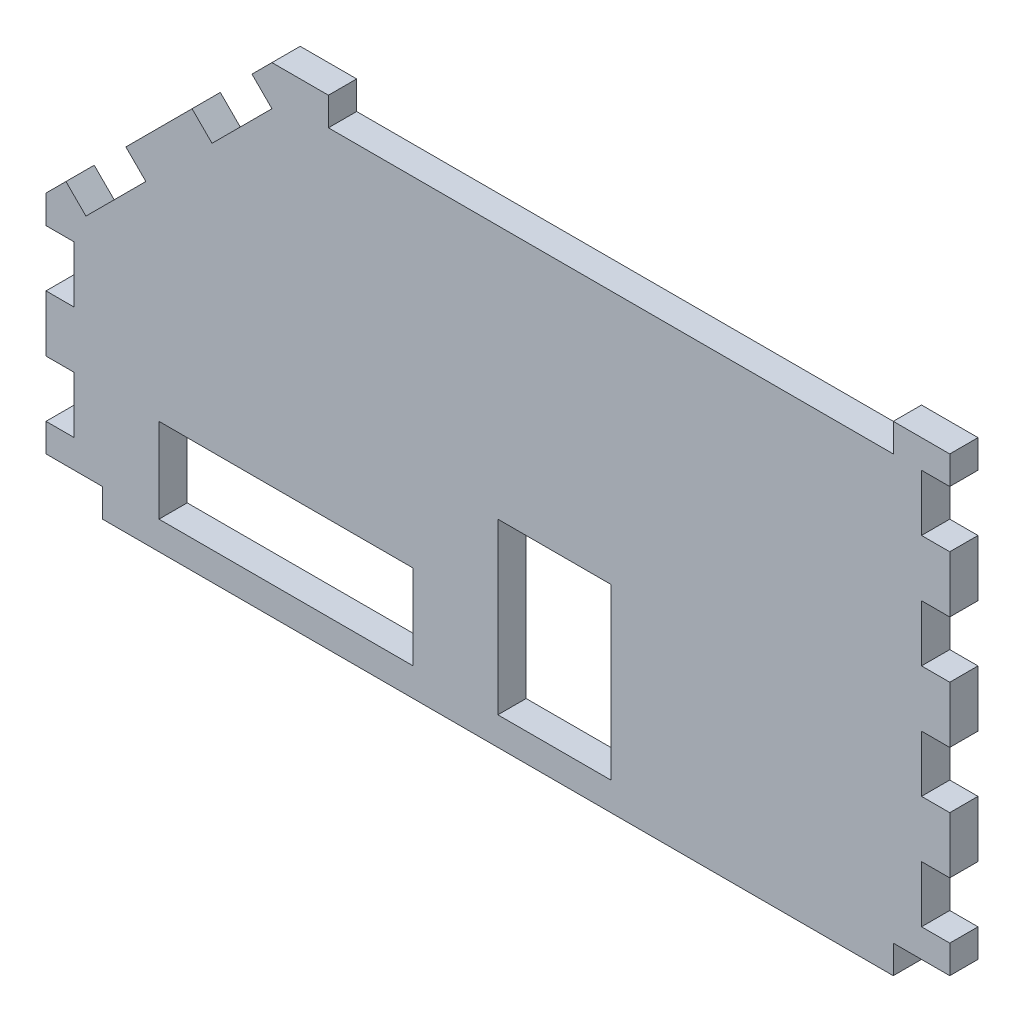
SolidWorks part; units mm, degrees
ref_plane "Plan de face" through (0, 0, 0) normal (0, 0, 1) x (1, 0, 0)
ref_plane "Plan de dessus" through (0, 0, 0) normal (0, 1, 0) x (1, 0, 0)
ref_plane "Plan de droite" through (0, 0, 0) normal (1, 0, 0) x (0, 0, -1)
sketch "Esquisse1" plane through (0, 0, 0) normal (0, 0, 1) x (1, 0, 0)
  line L0 (-80, 0) -> (-40, 40)
  line L4 (80, 40) -> (80, -40)
  line L6 (-70, -40) -> (-70, -45)
  line L7 (-70, -45) -> (70, -45)
  line L8 (70, -40) -> (70, -45)
  line L10 (-80, -25) -> (-75, -25)
  line L12 (-80, -35) -> (-75, -35)
  line L13 (-75, -25) -> (-75, -35)
  line L14 (-80, -5) -> (-75, -5)
  line L16 (-80, -15) -> (-75, -15)
  line L17 (-75, -5) -> (-75, -15)
  line L18 (-80, -40) -> (-80, -35)
  line L19 (-80, -5) -> (-80, 0)
  line L20 (-80, -25) -> (-80, -15)
  line L21 (-40, 40) -> (-30, 40)
  line L23 (-30, 40) -> (-30, 35)
  line L24 (-30, 35) -> (70, 35)
  line L25 (70, 40) -> (70, 35)
  line L26 (70, 40) -> (80, 40)
  line L27 (-80, -40) -> (-70, -40)
  line L28 (70, -40) -> (80, -40)
  dimension "D3" = 140
  dimension "D4" = 10
  dimension "D6" = 80
  dimension "D7" = 5
  dimension "D10" = 10
  dimension "D11" = 10
  dimension "D12" = 5
  dimension "D13" = 155
  dimension "D16" = 10
  dimension "D17" = 10
extrude "Boss.-Extru.1" add sketch "Esquisse1" along normal blind 5
sketch "Esquisse2" plane through (0, 0, 5) normal (0, 0, 1) x (1, 0, 0)
  line L0 (80, -40) -> (80, 40) construction
  line L1 (75, -25) -> (80, -25)
  line L2 (75, -25) -> (75, -35)
  line L3 (75, -35) -> (80, -35)
  line L4 (80, -25) -> (80, -35)
  line L5 (70, -40) -> (80, -40) construction
  line L6 (75, -5) -> (80, -5)
  line L7 (75, -5) -> (75, -15)
  line L8 (75, -15) -> (80, -15)
  line L9 (80, -5) -> (80, -15)
  line L10 (75, 15) -> (80, 15)
  line L11 (75, 15) -> (75, 5)
  line L12 (75, 5) -> (80, 5)
  line L13 (80, 15) -> (80, 5)
  line L14 (75, 35) -> (80, 35)
  line L15 (75, 35) -> (75, 25)
  line L16 (75, 25) -> (80, 25)
  line L17 (80, 35) -> (80, 25)
  dimension "D1" = 5
  dimension "D2" = 10
  dimension "D3" = 0
  dimension "D4" = 5
extrude "Enlèv. mat.-Extru.1" cut sketch "Esquisse2" against normal blind 10
sketch "Esquisse3" plane through (0, 0, 5) normal (0, 0, 1) x (1, 0, 0)
  line L0 (-43.5355, 36.4645) -> (-54.1421, 25.8579)
  line L1 (-43.5355, 36.4645) -> (-40, 32.9289)
  line L2 (-54.1421, 25.8579) -> (-50.6066, 22.3223)
  line L3 (-40, 32.9289) -> (-50.6066, 22.3223)
  line L4 (-40, 40) -> (-80, 0) construction
  line L5 (-65.8579, 14.1421) -> (-76.4645, 3.5355)
  line L6 (-65.8579, 14.1421) -> (-62.3223, 10.6066)
  line L7 (-76.4645, 3.5355) -> (-72.9289, 0)
  line L8 (-62.3223, 10.6066) -> (-72.9289, 0)
  point P6 (0, 0)
  dimension "D1" = 5
  dimension "D2" = 15
  dimension "D3" = 5
  dimension "D4" = 15
  dimension "D5" = 5
  dimension "D6" = 5
extrude "Enlèv. mat.-Extru.2" cut sketch "Esquisse3" against normal blind 10
sketch "Esquisse4" plane through (0, 0, 5) normal (0, 0, 1) x (1, 0, 0)
  line L0 (-70, -40) -> (70, -40) construction
  line L1 (-70, -40) -> (-70, -45) construction
  line L2 (-60, -40) -> (-15, -40)
  line L3 (-60, -40) -> (-60, -25)
  line L4 (-60, -25) -> (-15, -25)
  line L5 (-15, -40) -> (-15, -25)
  line L7 (0, -40) -> (20, -40)
  line L8 (0, -40) -> (0, -10)
  line L9 (0, -10) -> (20, -10)
  line L10 (20, -40) -> (20, -10)
  dimension "D1" = 10
  dimension "D2" = 45
  dimension "D3" = 15
  dimension "D4" = 15
  dimension "D5" = 20
  dimension "D6" = 30
extrude "Enlèv. mat.-Extru.3" cut sketch "Esquisse4" against normal blind 10
